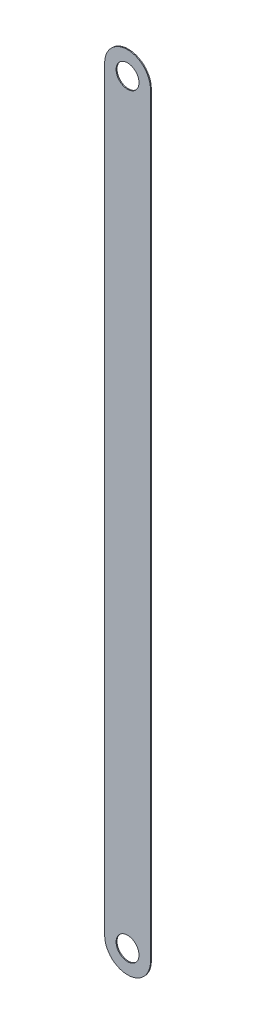
SolidWorks part; units mm, degrees
ref_plane "Front Plane" through (0, 0, 0) normal (0, 0, 1) x (1, 0, 0)
ref_plane "Top Plane" through (0, 0, 0) normal (0, 1, 0) x (1, 0, 0)
ref_plane "Right Plane" through (0, 0, 0) normal (1, 0, 0) x (0, 0, -1)
sketch "Sketch2" plane through (0, 0, 0) normal (0, 0, 1) x (1, 0, 0)
  line L0 (0, 209.55) -> (0, 0) construction
  line L1 (6.35, 209.55) -> (6.35, 0)
  line L2 (-6.35, 209.55) -> (-6.35, 0)
  arc A0 (6.35, 209.55) -> (-6.35, 209.55) centre (0, 209.55) ccw
  arc A1 (-6.35, 0) -> (6.35, 0) centre (0, 0) ccw
  circle A2 centre (0, 209.55) radius 3.175
  circle A3 centre (0, 0) radius 3.175
  point P3 (0, 104.775)
  dimension "D3" = 6.35
  dimension "D4" = 6.35
  dimension "D1" = 12.7
  dimension "D2" = 209.55
extrude "Boss-Extrude1" add sketch "Sketch2" along normal blind 0.254
scale "Scale1" scale about centroid uniform scaling yes scale factor 1.5
scale "Scale2" scale about centroid uniform scaling yes scale factor 1
scale "Scale3" scale about centroid uniform scaling yes scale factor 1.5
scale "Scale4" scale about centroid uniform scaling yes scale factor 1
scale "Scale5" scale about centroid uniform scaling yes scale factor 0.667
